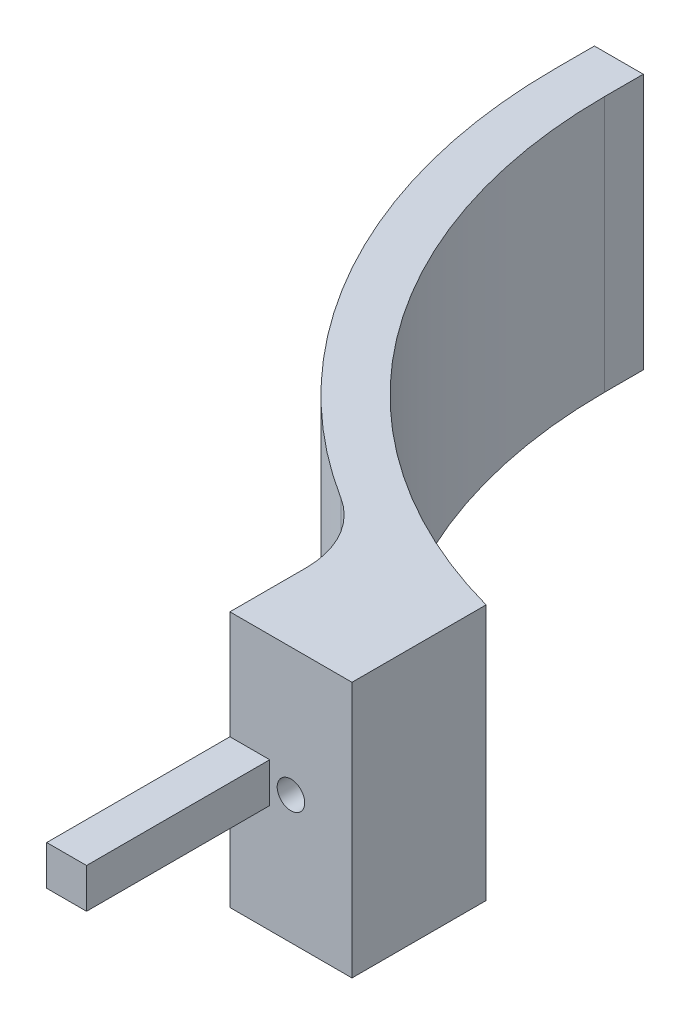
SolidWorks part; units mm, degrees
ref_plane "Front Plane" through (0, 0, 0) normal (0, 0, 1) x (1, 0, 0)
ref_plane "Top Plane" through (0, 0, 0) normal (0, 1, 0) x (1, 0, 0)
ref_plane "Right Plane" through (0, 0, 0) normal (1, 0, 0) x (0, 0, -1)
sketch "Sketch4" plane through (0, 0, 0) normal (0, 1, 0) x (1, 0, 0)
  line L0 (-185.6, 0) -> (-169.6, 0)
  line L4 (-44.8145, -163.5721) -> (-44.8145, -207.4949)
  line L5 (-44.8145, -207.4949) -> (-84.8, -207.4949)
  line L7 (-169.6, 0) -> (0, 0) construction
  line L8 (-84.8, 0) -> (-84.8, -264.5922) construction
  line L11 (-84.8, -165.0949) -> (-84.8, -207.4949)
  arc A0 (-169.6, 0) -> (-44.8145, -163.5721) centre (0, 0) ccw
  arc A1 (-185.6, 0) -> (-84.8, -165.0949) centre (0, 0) ccw
  point P11 (-84.8, -207.4949)
  dimension "D1" = 169.6
  dimension "D3" = 16
  dimension "D5" = 42.4
  dimension "D2" = 185.6
extrude "Boss-Extrude1" add sketch "Sketch4" against normal blind 83.8821
sketch "Sketch5" plane through (0, 0, 207.4949) normal (0, 0, 1) x (1, 0, 0)
  line L0 (-64.8073, 0) -> (-64.8072, -83.8821) construction
  line L1 (-84.8, 0) -> (-44.8145, 0) construction
  line L2 (-84.8, -83.8821) -> (-44.8145, -83.8821) construction
  circle A0 centre (-64.8073, -41.9411) radius 4.505
  dimension "D1" = 9.01
extrude "Cut-Extrude1" cut sketch "Sketch5" against normal blind 30 contours A0
sketch "Sketch6" plane through (0, 0, 0) normal (0, 0, -1) x (-1, 0, 0)
  line L1 (169.6, 0) -> (185.6, 0)
  line L2 (169.6, 0) -> (169.6, -83.8821)
  line L3 (169.6, -83.8821) -> (185.6, -83.8821)
  line L4 (185.6, 0) -> (185.6, -83.8821)
extrude "Boss-Extrude2" add sketch "Sketch6" along normal blind 12.7
fillet "Fillet1" radius 30 1 edges at (-84.8, -41.9411, 165.0949)
sketch "Sketch7" plane through (0, 0, 207.4949) normal (0, 0, 1) x (1, 0, 0)
  line L0 (-84.8, 0) -> (-84.8, -83.8821) construction
  line L1 (-84.8, -35.4411) -> (-71.76, -35.4411)
  line L2 (-84.8, -35.4411) -> (-84.8, -48.4411)
  line L3 (-84.8, -48.4411) -> (-71.76, -48.4411)
  line L4 (-71.76, -35.4411) -> (-71.76, -48.4411)
  line L5 (-84.8, -41.9411) -> (-44.8145, -41.9411) construction
  line L6 (-44.8145, -83.8821) -> (-44.8145, 0) construction
  dimension "D1" = 13
  dimension "D2" = 13.04
extrude "Boss-Extrude3" add sketch "Sketch7" along normal blind 60
sketch "Sketch8" plane through (-84.8, 0, 0) normal (-1, 0, 0) x (0, 0, 1)
  line L0 (207.4949, -35.4411) -> (207.4949, -48.4411) construction
  line L1 (207.4949, -41.9411) -> (227.4949, -41.9411) construction
  line L2 (227.4949, -41.9411) -> (247.4949, -41.9411) construction
  circle A0 centre (227.4949, -41.9411) radius 1.5
  circle A1 centre (247.4949, -41.9411) radius 1.5
  dimension "D1" = 3
  dimension "D2" = 3
  dimension "D3" = 20
  dimension "D4" = 20
extrude "Cut-Extrude2" cut sketch "Sketch8" against normal blind 10
equation "\"Waist\"= 33.92cm"
equation "\"D1@Sketch4\"=\"Waist\"/2"
equation "\"D3@Sketch4\" = \"frontplate_thickness\""
equation "\"D5@Sketch4\"=(\"Waist\"/2)*0.25"
equation "\"D1@Boss-Extrude1\" = \"frontplate_height\""
equation "\"D1@Sketch5\"=\"Dowelpin_diameter\"+0.01"
equation "\"D1@Boss-Extrude2\"=12.7mm"
equation "\"backplate_height\"=284.29500000"
equation "\"D2@Sketch4\"= ( \"Waist\" / 2 ) + \"frontplate_thickness\""
equation "\"Dowelpin_diameter\"= 9mm"
equation "\"frontplate_thickness\"=16.00000000"
equation "\"frontplate_height\"=83.88212687"
equation "\"backplate_thickness\"=10.60908672"
equation "\"backplate_width\"=133.00000000"
equation "\"hinge_diameter\"=9.54764209"
equation "\"hinge_height\"=83.88212687"
equation "\"adjustment_thickness\"=3.52061470"
equation "\"adjustment_height\"=28.42950000"
equation "\"Padding_Area1\"=1700.10510064"
equation "\"Padding_Area2\"=1700.10510064"
equation "\"Padding_Area3\"=377.80113348"
